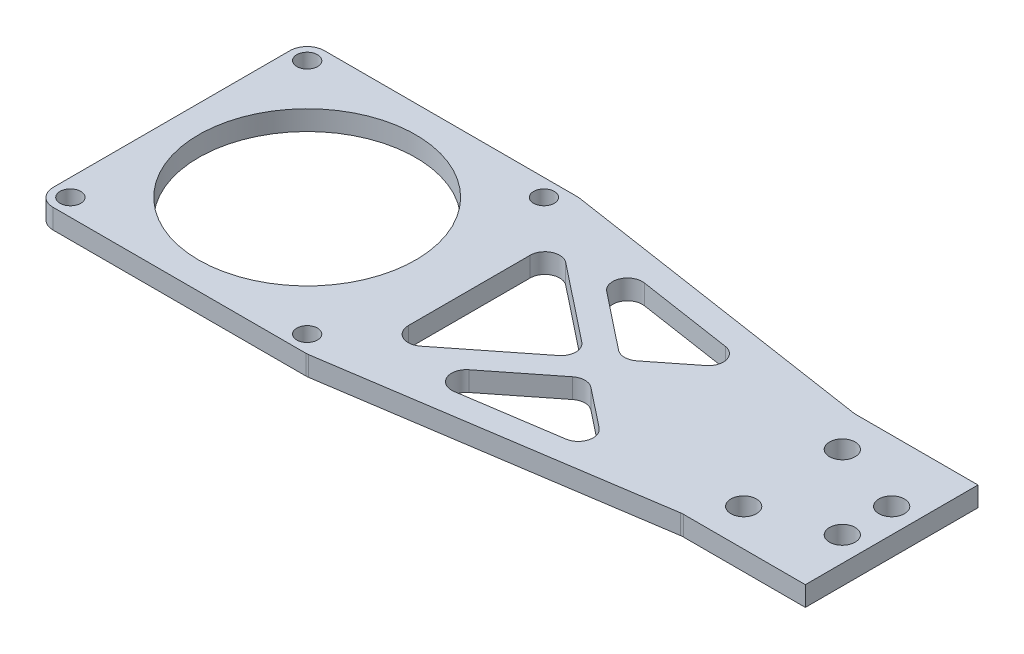
SolidWorks part; units mm, degrees
material "1060 合金"
ref_plane "前视基准面" through (0, 0, 0) normal (0, 0, 1) x (1, 0, 0)
ref_plane "上视基准面" through (0, 0, 0) normal (0, 1, 0) x (1, 0, 0)
ref_plane "右视基准面" through (0, 0, 0) normal (1, 0, 0) x (0, 0, -1)
sketch "草图1" plane through (0, 0, 0) normal (0, 1, 0) x (1, 0, 0)
  line L0 (0, 0) -> (7.5, 0)
  line L1 (-7.5, -10) -> (7.5, -10)
  line L2 (-7.5, -10) -> (-7.5, 10)
  line L3 (-7.5, 10) -> (7.5, 10)
  line L4 (7.5, -10) -> (7.5, 10)
  line L5 (-7.5, -10) -> (7.5, 10) construction
  line L6 (-7.5, 10) -> (7.5, -10) construction
  line L7 (7.5, -5) -> (7.5, 5)
  line L9 (12.5, 17.5) -> (-12.5, 17.5)
  line L10 (12.5, 17.5) -> (12.5, -17.5)
  line L11 (12.5, -17.5) -> (-12.5, -17.5)
  line L12 (-12.5, 17.5) -> (-12.5, -17.5)
  line L13 (12.5, 17.5) -> (-12.5, -17.5) construction
  line L14 (12.5, -17.5) -> (-12.5, 17.5) construction
  circle A0 centre (7.5, 5) radius 2.6
  circle A1 centre (7.5, -5) radius 2.6
  circle A2 centre (-7.5, -10) radius 2.6
  circle A3 centre (-7.5, 10) radius 2.6
  point P0 (0, 0)
  point P11 (7.5, 0)
  dimension "D3" = 10
  dimension "D4" = 5.2
  dimension "D5" = 5.2
  dimension "D6" = 5.2
  dimension "D7" = 5.2
  dimension "D1" = 20
  dimension "D2" = 15
  dimension "D8" = 7.5
  dimension "D9" = 5
extrude "凸台-拉伸1" add sketch "草图1" along normal blind 4
sketch "草图2" plane through (0, 4, 0) normal (0, 1, 0) x (1, 0, 0)
  line L0 (-22.5, 0) -> (0, 0)
  line L1 (-133.482, 27.5) -> (-78.482, 27.5)
  line L2 (-133.482, 27.5) -> (-133.482, -27.5)
  line L3 (-133.482, -27.5) -> (-78.482, -27.5)
  line L4 (-78.482, 27.5) -> (-78.482, -27.5)
  line L5 (-133.482, 27.5) -> (-78.482, -27.5) construction
  line L6 (-133.482, -27.5) -> (-78.482, 27.5) construction
  line L7 (-12.5, 17.5) -> (-12.5, -17.5) construction
  line L8 (-105.982, 0) -> (-22.5, 0)
  line L9 (-78.482, 27.5) -> (-12.5, 17.5)
  line L10 (-12.5, 17.5) -> (-12.5, -17.5)
  line L11 (-12.5, -17.5) -> (-78.482, -27.5)
  circle A0 centre (-22.5, 0) radius 6.0415
  circle A2 centre (-105.982, 0) radius 27.5
  circle A3 centre (-7.5, -10) radius 2.6 construction
  dimension "D1" = 12.0829
  dimension "D2" = 83.482
  dimension "D3" = 15
  dimension "D4" = 55
  dimension "D7" = 90
  dimension "D5" = 55
  dimension "D6" = 55
  dimension "D8" = 180
extrude "凸台-拉伸2" add sketch "草图2" against normal blind 4 separate body
combine bodies "组合1" operation type add bodies to combine 106 107
fillet "圆角1" radius 3.5 6 edges at (-12.5, 2, -17.5) (-78.482, 2, -27.5) (-133.482, 2, 27.5) (-78.482, 2, 27.5) (-12.5, 2, 17.5) (-133.482, 2, -27.5)
sketch "草图3" plane through (0, 4, 0) normal (0, 1, 0) x (1, 0, 0)
  line L0 (-129.982, 24) -> (-105.982, 0)
  line L1 (-105.982, 0) -> (-129.982, -24)
  line L2 (-133.482, 24) -> (-133.482, -24) construction
  circle A0 centre (-105.982, 0) radius 22
  dimension "D1" = 90
  dimension "D4" = 44
  dimension "D2" = 45
  dimension "D3" = 0
extrude "切除-拉伸1" cut sketch "草图3" against normal blind 10 contours L0 A0 L1 | L1 A0 L0
sketch "草图4" plane through (0, 4, 0) normal (0, 1, 0) x (1, 0, 0)
  line L0 (-93.6076, 12.3744) -> (-105.982, 0)
  line L2 (-133.482, 24) -> (-133.482, -24) construction
  line L4 (-129.982, 24) -> (-81.982, 24)
  line L5 (-129.982, 24) -> (-129.982, -24)
  line L6 (-129.982, -24) -> (-81.982, -24)
  line L7 (-81.982, 24) -> (-81.982, -24)
  line L8 (-129.982, 24) -> (-81.982, -24) construction
  line L9 (-129.982, -24) -> (-81.982, 24) construction
  circle A0 centre (-105.982, 0) radius 17.5
  circle A1 centre (-93.6076, 12.3744) radius 2.1
  circle A2 centre (-81.982, 24) radius 2.1
  dimension "D1" = 35
  dimension "D2" = 4.2
  dimension "D6" = 4.2
  dimension "D3" = 45
  dimension "D4" = 48
  dimension "D5" = 48
extrude "切除-拉伸2" cut sketch "草图4" against normal blind 10 contours L4 A2 L7 | L7 A2 L4
pattern_circular "阵列(圆周)1" count 4 over 360 about axis through (-105.982, 0, 0) along (0, 1, 0) of "切除-拉伸2"
sketch "草图5" plane through (0, 82, 0) normal (0, 1, 0) x (1, 0, 0)
  line L3 (-43.8587, 4.7173) -> (-36.0249, 10.9009)
  line L4 (-59.1004, 13.8366) -> (-47.579, 4.7195)
  line L5 (-37.4342, 16.2218) -> (-56.7892, 19.1552)
  line L6 (-43.8587, 4.7173) -> (-36.0249, 10.9009)
  line L7 (-59.1004, 13.8366) -> (-47.579, 4.7195)
  line L8 (-37.4342, 16.2218) -> (-56.7892, 19.1552)
  line L9 (-35.9146, -10.8869) -> (-43.8643, -4.5962)
  line L10 (-57.0283, -19.1915) -> (-37.3267, -16.2055)
  line L11 (-47.5846, -4.5939) -> (-59.3366, -13.8706)
  line L12 (-35.9146, -10.8869) -> (-43.8643, -4.5962)
  line L13 (-57.0283, -19.1915) -> (-37.3267, -16.2055)
  line L14 (-47.5846, -4.5939) -> (-59.3366, -13.8706)
  line L15 (-68.3625, -14.6252) -> (-52.7329, -2.2878)
  line L16 (-73.2213, 12.435) -> (-73.2213, -12.2705)
  line L17 (-52.7301, 2.4195) -> (-68.3597, 14.7875)
  line L18 (-68.3625, -14.6252) -> (-52.7329, -2.2878)
  line L19 (-73.2213, 12.435) -> (-73.2213, -12.2705)
  line L20 (-52.7301, 2.4195) -> (-68.3597, 14.7875)
  arc A3 (-47.579, 4.7195) -> (-43.8587, 4.7173) centre (-45.7174, 7.072) ccw
  arc A4 (-56.7892, 19.1552) -> (-59.1004, 13.8366) centre (-57.2388, 16.1891) ccw
  arc A5 (-36.0249, 10.9009) -> (-37.4342, 16.2218) centre (-37.8837, 13.2557) ccw
  arc A6 (-47.579, 4.7195) -> (-43.8587, 4.7173) centre (-45.7174, 7.072) ccw
  arc A7 (-56.7892, 19.1552) -> (-59.1004, 13.8366) centre (-57.2388, 16.1891) ccw
  arc A8 (-36.0249, 10.9009) -> (-37.4342, 16.2218) centre (-37.8837, 13.2557) ccw
  arc A9 (-37.3267, -16.2055) -> (-35.9146, -10.8869) centre (-37.7762, -13.2394) ccw
  arc A10 (-59.3366, -13.8706) -> (-57.0283, -19.1915) centre (-57.4778, -16.2253) ccw
  arc A11 (-43.8643, -4.5962) -> (-47.5846, -4.5939) centre (-45.7259, -6.9487) ccw
  arc A12 (-37.3267, -16.2055) -> (-35.9146, -10.8869) centre (-37.7762, -13.2394) ccw
  arc A13 (-59.3366, -13.8706) -> (-57.0283, -19.1915) centre (-57.4778, -16.2253) ccw
  arc A14 (-43.8643, -4.5962) -> (-47.5846, -4.5939) centre (-45.7259, -6.9487) ccw
  arc A15 (-73.2213, -12.2705) -> (-68.3625, -14.6252) centre (-70.2213, -12.2705) ccw
  arc A16 (-68.3597, 14.7875) -> (-73.2213, 12.435) centre (-70.2213, 12.435) ccw
  arc A17 (-52.7329, -2.2878) -> (-52.7301, 2.4195) centre (-54.5917, 0.067) ccw
  arc A18 (-73.2213, -12.2705) -> (-68.3625, -14.6252) centre (-70.2213, -12.2705) ccw
  arc A19 (-68.3597, 14.7875) -> (-73.2213, 12.435) centre (-70.2213, 12.435) ccw
  arc A20 (-52.7329, -2.2878) -> (-52.7301, 2.4195) centre (-54.5917, 0.067) ccw
  dimension "D1" = 0
  dimension "D2" = 0
  dimension "D3" = 0
extrude "切除-拉伸3" cut sketch "草图5" against normal blind 163
